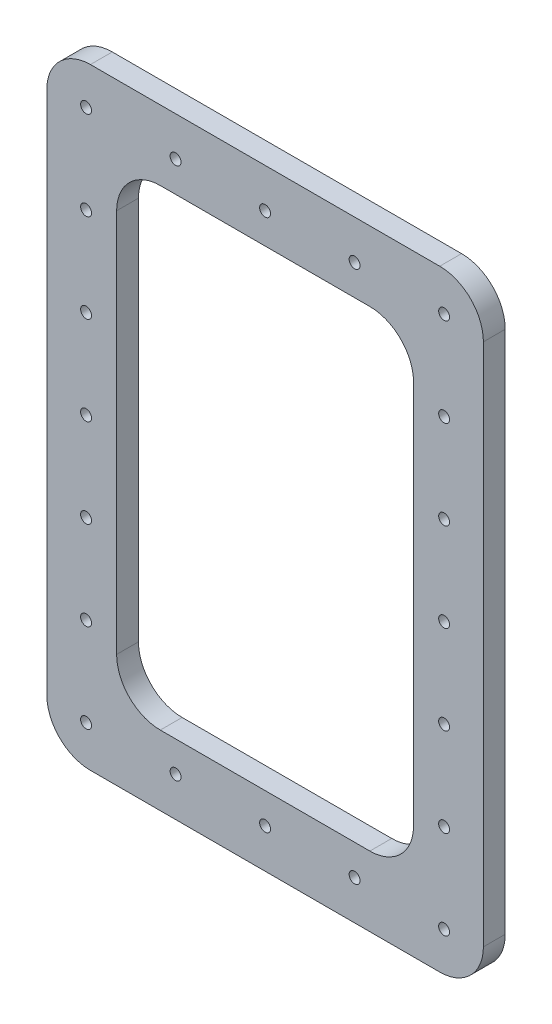
SolidWorks part; units mm, degrees
ref_plane "Front Plane" through (0, 0, 0) normal (0, 0, 1) x (1, 0, 0)
ref_plane "Top Plane" through (0, 0, 0) normal (0, 1, 0) x (1, 0, 0)
ref_plane "Right Plane" through (0, 0, 0) normal (1, 0, 0) x (0, 0, -1)
sketch "Sketch1" plane through (0, 0, 0) normal (0, 0, 1) x (1, 0, 0)
  line L0 (0, 0) -> (-41, 0) construction
  line L1 (-50, -70) -> (50, -70)
  line L2 (-50, -70) -> (-50, 70)
  line L3 (-50, 70) -> (50, 70)
  line L4 (50, -70) -> (50, 70)
  line L5 (-50, -70) -> (50, 70) construction
  line L6 (-50, 70) -> (50, -70) construction
  line L7 (-41, -61) -> (41, -61) construction
  line L8 (-41, -61) -> (-41, 61) construction
  line L9 (-41, 61) -> (41, 61) construction
  line L10 (41, -61) -> (41, 61) construction
  line L11 (-41, -61) -> (41, 61) construction
  line L12 (-41, 61) -> (41, -61) construction
  line L13 (0, 0) -> (0, 44.6853) construction
  line L15 (-34, -54) -> (34, -54)
  line L16 (-34, -54) -> (-34, 54)
  line L17 (-34, 54) -> (34, 54)
  line L18 (34, -54) -> (34, 54)
  line L19 (-34, -54) -> (34, 54) construction
  line L20 (-34, 54) -> (34, -54) construction
  circle A0 centre (0, 61) radius 1.25
  circle A1 centre (-41, 61) radius 1.25
  circle A2 centre (-20.5, 61) radius 1.25
  circle A3 centre (20.5, 61) radius 1.25
  circle A4 centre (41, 61) radius 1.25
  circle A5 centre (-41, 0) radius 1.25
  circle A6 centre (-41, 40.6667) radius 1.25
  circle A7 centre (-41, 20.3333) radius 1.25
  circle A8 centre (41, 40.6667) radius 1.25
  circle A9 centre (41, 20.3333) radius 1.25
  circle A10 centre (41, 0) radius 1.25
  circle A11 centre (-20.5, -61) radius 1.25
  circle A12 centre (0, -61) radius 1.25
  circle A13 centre (20.5, -61) radius 1.25
  circle A14 centre (41, -61) radius 1.25
  circle A15 centre (41, -40.6667) radius 1.25
  circle A16 centre (41, -20.3333) radius 1.25
  circle A17 centre (-41, -20.3333) radius 1.25
  circle A18 centre (-41, -40.6667) radius 1.25
  circle A19 centre (-41, -61) radius 1.25
  point P0 (0, 0)
  point P6 (0, 0)
  dimension "D5" = 20.5
  dimension "D7" = 2.5
  dimension "D1" = 100
  dimension "D2" = 140
  dimension "D3" = 9
  dimension "D4" = 9
  dimension "D6" = 20.5
  dimension "D8" = 20.3333
  dimension "D9" = 20.3333
  dimension "D10" = 16
  dimension "D11" = 16
extrude "Boss-Extrude1" add sketch "Sketch1" along normal blind 5
fillet "Fillet1" radius 10 8 edges at (-34, 54, 2.5) (34, 54, 2.5) (-50, -70, 2.5) (34, -54, 2.5) (-34, -54, 2.5) (50, -70, 2.5) (-50, 70, 2.5) (50, 70, 2.5)
